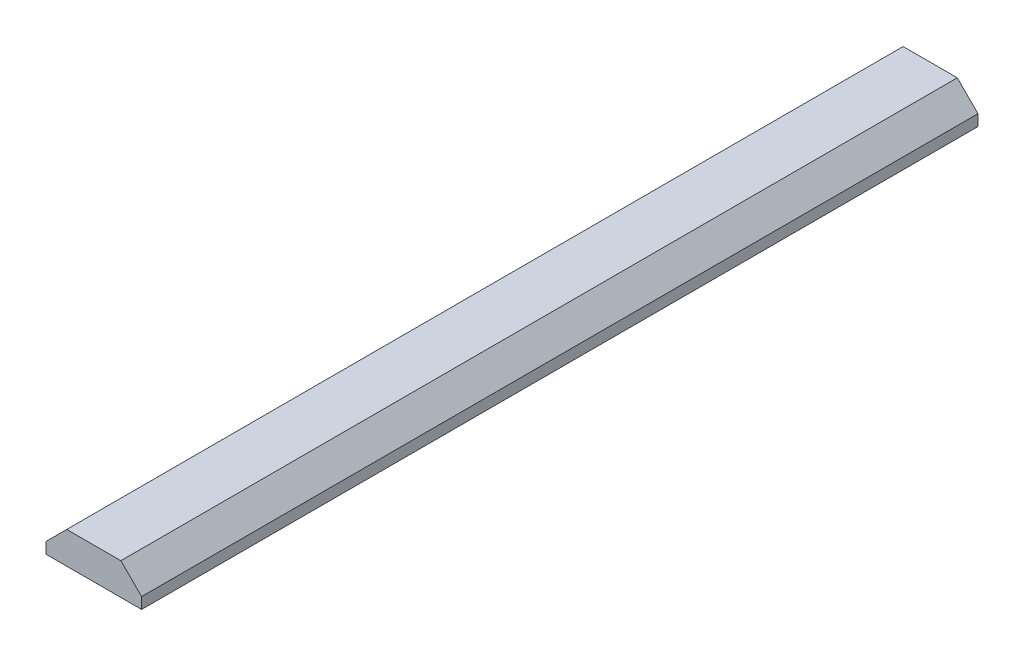
SolidWorks part; units mm, degrees
ref_plane "Ebene vorne" through (0, 0, 0) normal (0, 0, 1) x (1, 0, 0)
ref_plane "Ebene oben" through (0, 0, 0) normal (0, 1, 0) x (1, 0, 0)
ref_plane "Ebene rechts" through (0, 0, 0) normal (1, 0, 0) x (0, 0, -1)
sketch "Skizze1" plane through (0, 0, 0) normal (0, 0, 1) x (1, 0, 0)
  line L0 (0, 0) -> (0, 23680.6173) construction
  line L1 (3.4, 1.8089) -> (-3.4, 1.8089)
  line L2 (-3.4, 1.8089) -> (-6, -0.7911)
  line L3 (-6, -0.7911) -> (-6, -2.1911)
  line L4 (-6, -2.1911) -> (6, -2.1911)
  line L5 (6, -0.7911) -> (6, -2.1911)
  line L6 (3.4, 1.8089) -> (6, -0.7911)
  point P9 (0, -2.1911)
  point P11 (0, 1.8089)
  dimension "D1" = 3.4
  dimension "D2" = 6
  dimension "D3" = 4
  dimension "D4" = 135
extrude "Aufsatz-Linear austragen1" add sketch "Skizze1" along normal blind 105 contours L1 L2 L3 L4 L5 L6
